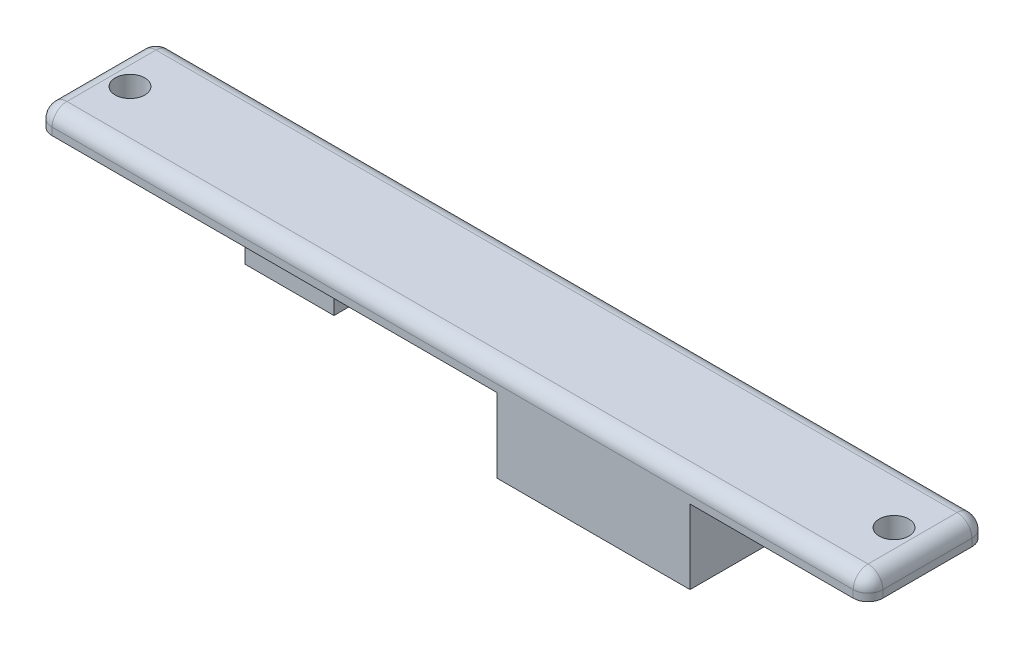
SolidWorks part; units mm, degrees
ref_plane "Front Plane" through (0, 0, 0) normal (0, 0, 1) x (1, 0, 0)
ref_plane "Top Plane" through (0, 0, 0) normal (0, 1, 0) x (1, 0, 0)
ref_plane "Right Plane" through (0, 0, 0) normal (1, 0, 0) x (0, 0, -1)
sketch "Sketch1" plane through (0, 0, 0) normal (0, 1, 0) x (1, 0, 0)
  line L1 (-28, 4) -> (28, 4)
  line L2 (-28, 4) -> (-28, -4)
  line L3 (-28, -4) -> (28, -4)
  line L4 (28, 4) -> (28, -4)
  line L5 (-28, 4) -> (28, -4) construction
  line L6 (-28, -4) -> (28, 4) construction
  point P0 (0, 0)
  dimension "D1" = 56
  dimension "D2" = 8
extrude "Boss-Extrude1" add sketch "Sketch1" along normal blind 1.5 contours L1 L4 L3 L2
sketch "Sketch2" plane through (0, 1.5, 0) normal (0, 1, 0) x (1, 0, 0)
  circle A0 centre (-25.75, 0) radius 1
  circle A1 centre (25.75, 0) radius 1
  point P4 (0, 0)
  dimension "D3" = 2
  dimension "D1" = 51.5
  dimension "D2" = 25.75
extrude "Cut-Extrude1" cut sketch "Sketch2" against normal through all both and the other way through all
fillet "Fillet1" radius 1 8 edges at (-28, 1.5, 0) (0, 1.5, -4) (28, 1.5, 0) (0, 1.5, 4) (28, 0.75, -4) (28, 0.75, 4) (-28, 0.75, 4) (-28, 0.75, -4)
sketch "Sketch3" plane through (0, 0, 0) normal (0, -1, 0) x (1, 0, 0)
  line L0 (-27, 4) -> (27, 4) construction
  line L1 (3, 4) -> (16, 4)
  line L2 (3, 4) -> (3, -4)
  line L3 (3, -4) -> (16, -4)
  line L4 (16, 4) -> (16, -4)
  line L5 (-27, -4) -> (27, -4) construction
  line L6 (28, -3) -> (28, 3) construction
  line L7 (-28, -3) -> (-28, 3) construction
  line L8 (-18, -4) -> (-12, -4)
  line L9 (-18, -4) -> (-18, 0)
  line L10 (-18, 0) -> (-12, 0)
  line L11 (-12, -4) -> (-12, 0)
  dimension "D1" = 12
  dimension "D2" = 25
  dimension "D3" = 4
  dimension "D4" = 6
  dimension "D5" = 10
extrude "Boss-Extrude2" add sketch "Sketch3" along normal blind 5
